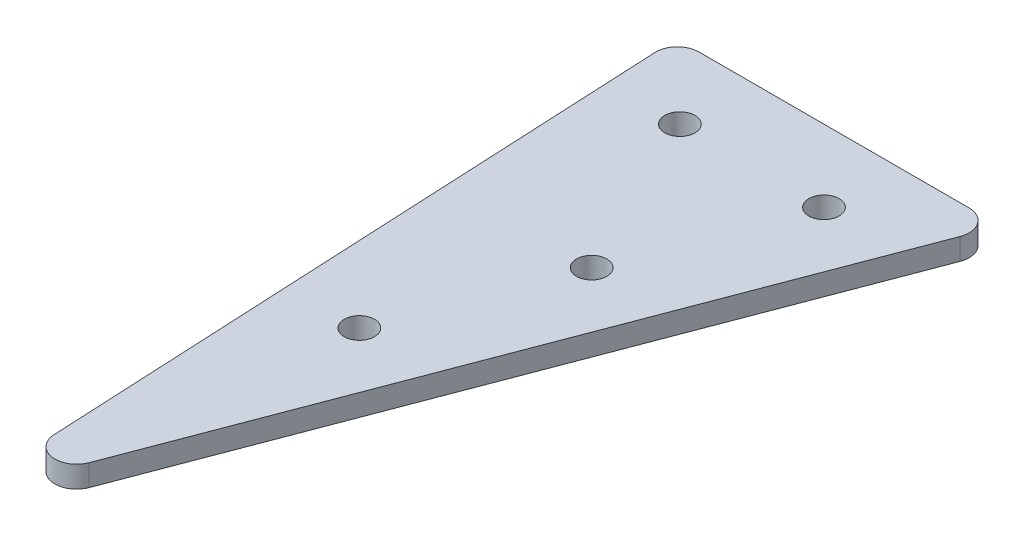
SolidWorks part; units mm, degrees
material "A-玻璃纤维"
ref_plane "前视基准面" through (0, 0, 0) normal (0, 0, 1) x (1, 0, 0)
ref_plane "上视基准面" through (0, 0, 0) normal (0, 1, 0) x (1, 0, 0)
ref_plane "右视基准面" through (0, 0, 0) normal (1, 0, 0) x (0, 0, -1)
sketch "草图1" plane through (0, 0, 0) normal (0, 1, 0) x (1, 0, 0)
  line L0 (-20, 0) -> (0, 0) construction
  line L1 (0, 0) -> (-17.739, -46.7475) construction
  line L2 (-20, 0) -> (-17.739, -46.7475) construction
  line L3 (-30.4953, 10) -> (14.4904, 10)
  line L4 (14.4904, 10) -> (-25.4098, -95.1485)
  line L5 (-30.4953, 10) -> (-25.4098, -95.1485)
  circle A0 centre (0, 0) radius 2.1
  circle A1 centre (-20, 0) radius 2.1
  circle A2 centre (-8.8695, -23.3737) radius 2.1
  circle A3 centre (-17.739, -46.7475) radius 2.1
  dimension "D2" = 4.2
  dimension "D3" = 20
  dimension "D4" = 25
  dimension "D5" = 25
  dimension "D1" = 69.22
  dimension "D6" = 10
extrude "凸台-拉伸1" add sketch "草图1" along normal blind 3
fillet "圆角1" radius 3 3 edges at (-30.4953, 1.5, -10) (-25.4098, 1.5, 95.1485) (14.4904, 1.5, -10)
